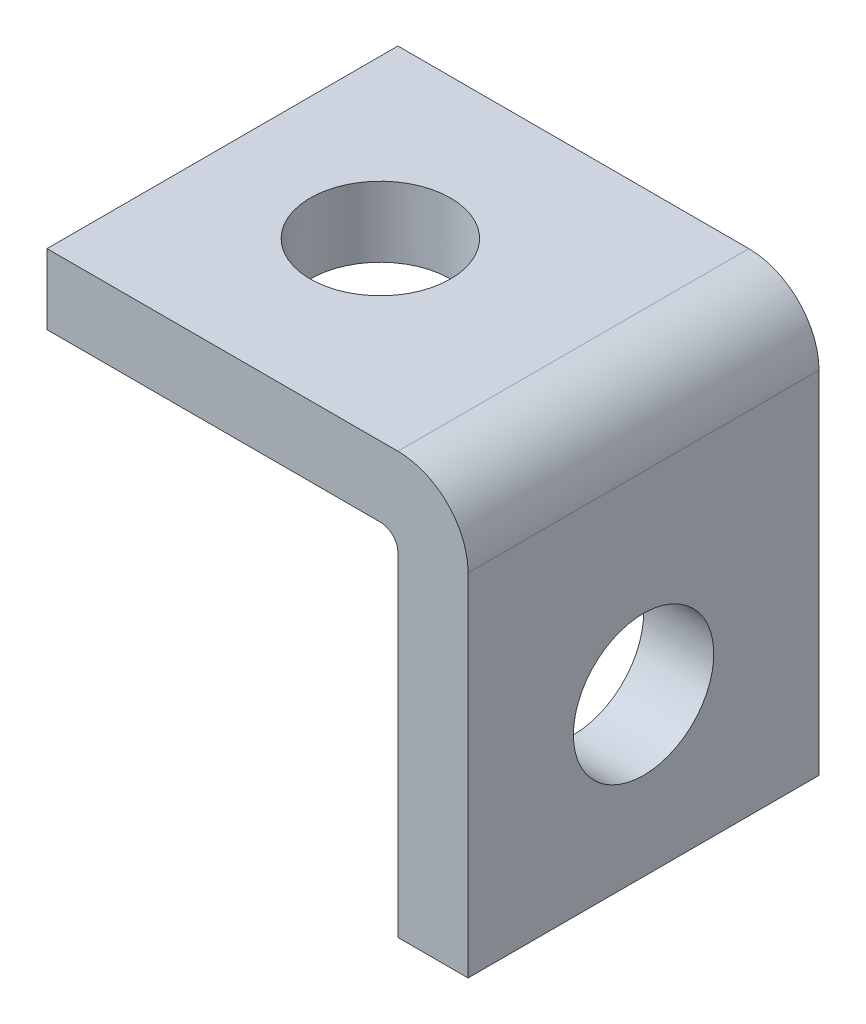
SolidWorks part; units mm, degrees
ref_plane "Plan de face" through (0, 0, 0) normal (0, 0, 1) x (1, 0, 0)
ref_plane "Plan de dessus" through (0, 0, 0) normal (0, 1, 0) x (1, 0, 0)
ref_plane "Plan de droite" through (0, 0, 0) normal (1, 0, 0) x (0, 0, -1)
sketch "Esquisse2" plane through (0, 0, 0) normal (0, 0, 1) x (1, 0, 0)
  line L0 (0, 12) -> (12, 12)
  line L1 (12, 12) -> (12, 0)
  line L2 (12, 0) -> (10, 0)
  line L3 (10, 0) -> (10, 10)
  line L4 (10, 10) -> (0, 10)
  line L5 (0, 10) -> (0, 12)
  line L6 (0, 0) -> (0, 10) construction
  line L7 (0, 0) -> (10, 0) construction
  dimension "D1" = 12
  dimension "D2" = 10
extrude "Boss.-Extru.2" add sketch "Esquisse2" along normal blind 10
sketch "Esquisse3" plane through (10, 0, 0) normal (-1, 0, 0) x (0, 0, 1)
  circle A0 centre (5, 4.5) radius 2
  dimension "D1" = 4
  dimension "D2" = 4.5
  dimension "D3" = 5
extrude "Enlèv. mat.-Extru.1" cut sketch "Esquisse3" against normal up to next
sketch "Esquisse4" plane through (0, 10, 0) normal (0, -1, 0) x (1, 0, 0)
  circle A0 centre (4.5, 5) radius 2
  dimension "D1" = 4
  dimension "D2" = 4.5
  dimension "D3" = 5
extrude "Enlèv. mat.-Extru.2" cut sketch "Esquisse4" against normal up to next
fillet "Congé1" radius 2 1 edges at (12, 12, 5)
fillet "Congé2" radius 0.5 1 edges at (10, 10, 5)
